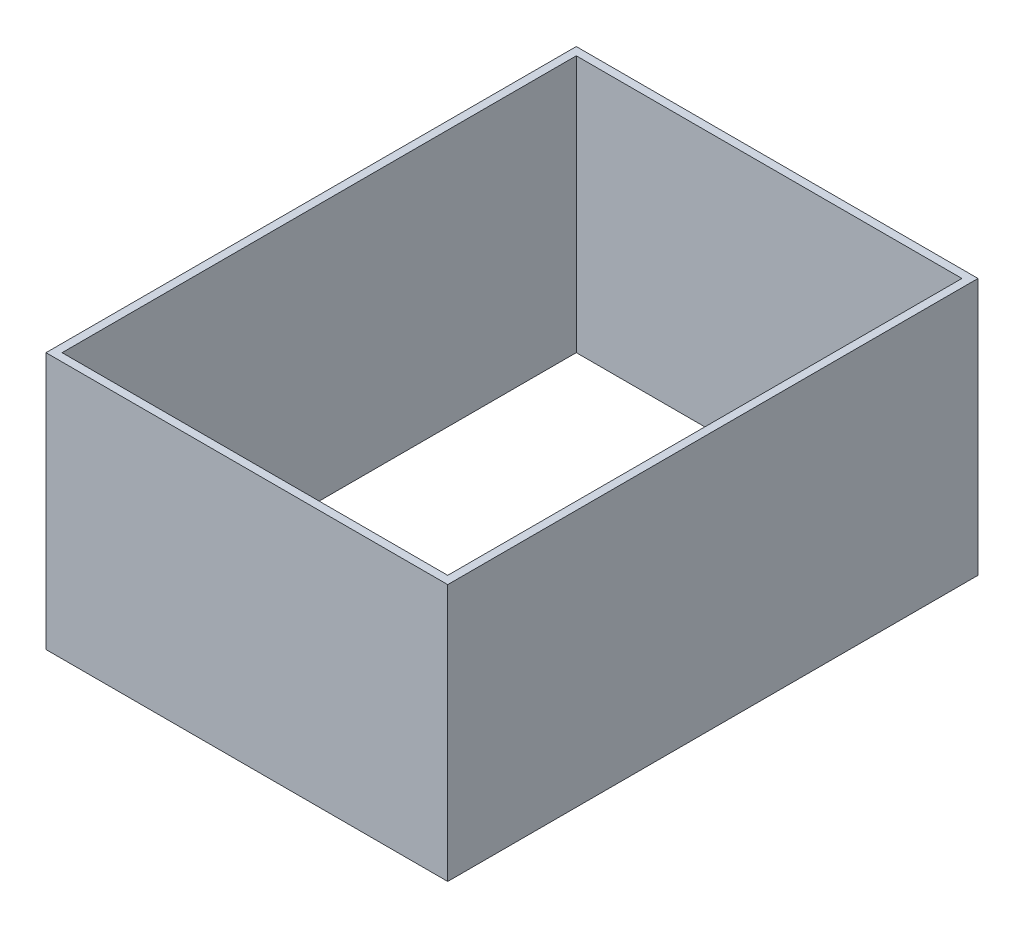
SolidWorks part; units mm, degrees
ref_plane "Front Plane" through (0, 0, 0) normal (0, 0, 1) x (1, 0, 0)
ref_plane "Top Plane" through (0, 0, 0) normal (0, 1, 0) x (1, 0, 0)
ref_plane "Right Plane" through (0, 0, 0) normal (1, 0, 0) x (0, 0, -1)
sketch "Sketch1" plane through (0, 0, 0) normal (0, 1, 0) x (1, 0, 0)
  line L1 (-76.2, -101.6) -> (76.2, -101.6)
  line L2 (-76.2, -101.6) -> (-76.2, 101.6)
  line L3 (-76.2, 101.6) -> (76.2, 101.6)
  line L4 (76.2, -101.6) -> (76.2, 101.6)
  line L5 (-76.2, -101.6) -> (76.2, 101.6) construction
  line L6 (-76.2, 101.6) -> (76.2, -101.6) construction
  point P0 (0, 0)
  dimension "D1" = 152.4
  dimension "D2" = 203.2
extrude "Boss-Extrude1" add sketch "Sketch1" along normal blind 101.6
shell "Shell1" thickness 3.175
